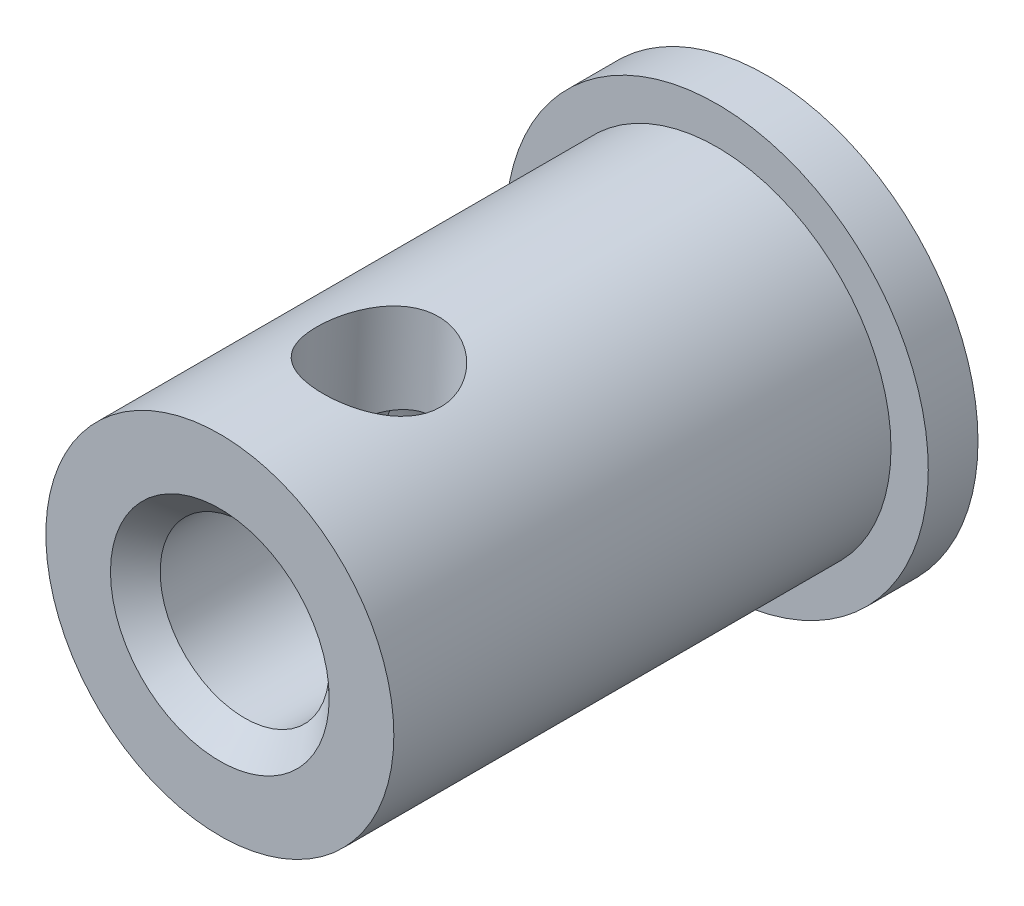
SolidWorks part; units mm, degrees
ref_plane "Спереди" through (0, 0, 0) normal (0, 0, 1) x (1, 0, 0)
ref_plane "Сверху" through (0, 0, 0) normal (0, 1, 0) x (1, 0, 0)
ref_plane "Справа" through (0, 0, 0) normal (1, 0, 0) x (0, 0, -1)
sketch "Эскиз1" plane through (0, 0, 0) normal (0, 0, 1) x (1, 0, 0)
  circle A0 centre (0, 0) radius 4.25
  dimension "D1" = 8.5
extrude "Бобышка-Вытянуть1" add sketch "Эскиз1" along normal blind 1
sketch "Эскиз2" plane through (0, 0, 1) normal (0, 0, 1) x (1, 0, 0)
  circle A0 centre (0, 0) radius 3.5
  dimension "D1" = 7
extrude "Бобышка-Вытянуть2" add sketch "Эскиз2" along normal blind 10
hole_wizard "Отверстие с зазором M31" positions "Эскиз8" profile "Эскиз10" hole size "M3" standard "ISO"
sketch "Эскиз8" plane through (0, 0, 11) normal (0, 0, 1) x (1, 0, 0)
  point P0 (0, 0)
sketch "Эскиз10" plane through (0, 0, 11) normal (1, 0, 0) x (0, -1, 0)
  line L0 (0, 0) -> (0, 6.0215)
  line L1 (0, 6.0215) -> (1.7, 5)
  line L2 (1.7, 5) -> (1.7, 0)
  line L5 (1.7, 0) -> (0, 0)
  line L10 (0, 6.0215) -> (-1.7, 5) construction
  line L11 (0, -6.35) -> (0, 107.95) construction
  dimension "Диаметр отверстия" = 3.4
  dimension "Глубина отверстия" = 5
  dimension "Угол заточки сверла" = 118
chamfer "Фаска1" distance 0.5 angle 45 1 edges at (1.7, 0, 11)
hole_wizard "Отверстие обработанное метчиком M31" positions "Трехмерный эскиз1" profile "Эскиз11" tap size "M3" standard "ISO"
sketch3d "Трехмерный эскиз1"
  point P0 (0.2069, 3.4939, 8)
  dimension "D1" = 3
sketch "Эскиз11" plane through (0.2069, 3.4939, 8) normal (0, 0, 1) x (-0.9983, 0.0591, 0)
  line L0 (0, 0) -> (0, 3.7511)
  line L1 (0, 3.7511) -> (1.25, 3)
  line L2 (1.25, 3) -> (1.25, 0)
  line L5 (1.25, 0) -> (0, 0)
  line L10 (0, 3.7511) -> (-1.25, 3) construction
  line L11 (0, -6.35) -> (0, 107.95) construction
  dimension "Диаметр сверла" = 2.5
  dimension "Глубина сверла" = 3
  dimension "Угол заточки сверла" = 118
cosmetic thread "Отверстие резьбы2" parameters "D1"=2.3478, "D2"=3
